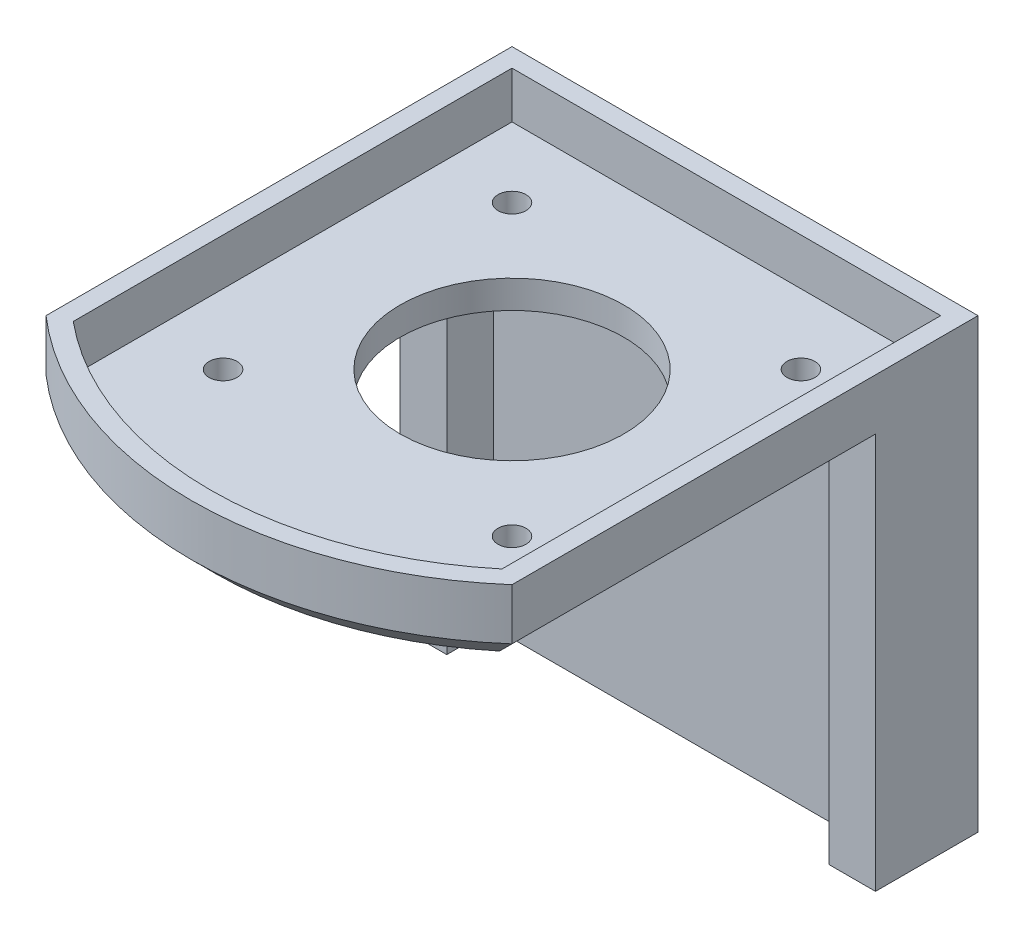
SolidWorks part; units mm, degrees
material "5052-H36"
ref_plane "前视基准面" through (0, 0, 0) normal (0, 0, 1) x (1, 0, 0)
ref_plane "上视基准面" through (0, 0, 0) normal (0, 1, 0) x (1, 0, 0)
ref_plane "右视基准面" through (0, 0, 0) normal (1, 0, 0) x (0, 0, -1)
sketch "草图1" plane through (0, 0, 0) normal (0, 1, 0) x (1, 0, 0)
  line L7 (0, 0) -> (0, -28.6182)
  line L9 (-25, -28.6182) -> (25, -28.6182)
  line L10 (25, -28.6182) -> (25, 21.3818)
  line L11 (-25, -28.6182) -> (-25, 21.3818)
  line L12 (-25, 21.3818) -> (25, 21.3818)
  circle A0 centre (0, 0) radius 38
extrude "凸台-拉伸1" add sketch "草图1" along normal blind 3
sketch "草图28" plane through (0, 3, 0) normal (0, 1, 0) x (1, 0, 0)
  line L0 (-25, -28.6182) -> (25, -28.6182)
  line L1 (0, -3.6182) -> (0, 11.8818)
  line L2 (15.5, -19.1182) -> (-15.5, -19.1182)
  line L3 (0, 11.8818) -> (15.5, 11.8818)
  line L4 (15.5, 11.8818) -> (15.5, -19.1182)
  line L5 (-15.5, -19.1182) -> (-15.5, 11.8818)
  line L6 (0, -28.6182) -> (0, -3.6182)
  circle A5 centre (0, -3.6182) radius 12
  circle A6 centre (15.5, 11.8818) radius 1.5
  circle A7 centre (15.5, -19.1182) radius 1.5
  circle A8 centre (-15.5, -19.1182) radius 1.5
  circle A9 centre (-15.5, 11.8818) radius 1.5
extrude "切除-拉伸9" cut sketch "草图28" against normal blind 4
sketch "草图30" plane through (0, 3, 0) normal (0, 1, 0) x (1, 0, 0)
  line L0 (-25, -28.6182) -> (-25, 21.3818)
  line L1 (-25, 21.3818) -> (25, 21.3818)
  line L2 (25, 21.3818) -> (25, -28.6182)
  line L3 (-25, -28.6182) -> (-23, -28.6182)
  line L4 (-23, -28.6182) -> (-23, 19.3818)
  line L5 (-23, 19.3818) -> (23, 19.3818)
  line L6 (23, 19.3818) -> (23, -28.6182)
  circle A0 centre (0, 0) radius 38
  circle A1 centre (0, 0) radius 36
extrude "凸台-拉伸11" add sketch "草图30" along normal blind 5
sketch "草图31" plane through (0, 0, 0) normal (0, -1, 0) x (1, 0, 0)
  line L0 (-25, -21.3818) -> (-25, -15.3818)
  line L1 (-25, 28.6182) -> (-25, -21.3818) construction
sketch "草图32" plane through (0, 0, 0) normal (0, -1, 0) x (1, 0, 0)
  line L0 (-25, -21.3818) -> (-25, -9.3818)
  line L1 (-25, 28.6182) -> (-25, -21.3818) construction
  line L3 (25, 28.6182) -> (25, -21.3818) construction
  line L4 (25, -10.3818) -> (25, -21.3818)
  line L5 (25, -21.3818) -> (-25, -21.3818)
  line L6 (-25, -9.3818) -> (-20, -9.3818)
  line L7 (-20, -9.3818) -> (-20, -14.3818)
  line L8 (-20, -14.3818) -> (20, -14.3818)
  line L9 (20, -14.3818) -> (20, -10.3818)
  line L10 (20, -10.3818) -> (25, -10.3818)
extrude "凸台-拉伸14" add sketch "草图32" along normal blind 40
sketch "草图33" plane through (0, 0, -21.3818) normal (0, 0, -1) x (-1, 0, 0)
  line L0 (0, 8) -> (0, -40)
  line L1 (-25, 8) -> (25, 8) construction
  line L2 (25, -40) -> (-25, -40) construction
  line L4 (5, -16) -> (2.5, -11.6699)
  line L5 (2.5, -11.6699) -> (-2.5, -11.6699)
  line L6 (-2.5, -11.6699) -> (-5, -16)
  line L7 (-5, -16) -> (-2.5, -20.3301)
  line L8 (-2.5, -20.3301) -> (2.5, -20.3301)
  line L9 (2.5, -20.3301) -> (5, -16)
  circle A0 centre (0, -16) radius 4.3301 construction
extrude "切除-拉伸12" cut sketch "草图33" against normal blind 4 contours L7 L8 L0 L5 L6 | L8 L9 L4 L5 L0
sketch "草图34" plane through (0, 0, -17.3818) normal (0, 0, -1) x (-1, 0, 0)
  line L0 (-5, -16) -> (5, -16)
  circle A0 centre (0, -16) radius 1.5
extrude "切除-拉伸13" cut sketch "草图34" against normal blind 4 contours A0
chamfer "倒角1" distance 2.5 angle 45 1 edges at (25, 0, 9.1182)
chamfer "倒角2" distance 2.5 angle 45 1 edges at (-25, 0, 9.6182)
chamfer "倒角3" distance 2.5 angle 45 1 edges at (0, 0, 38)
